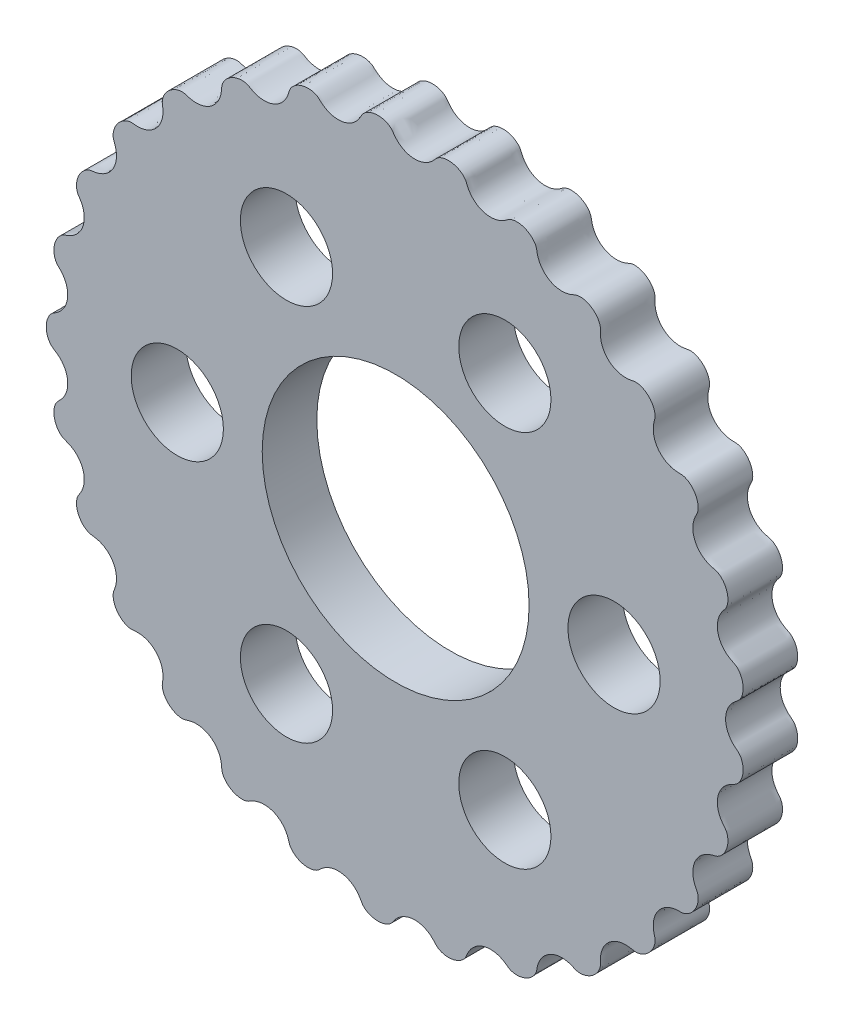
SolidWorks part; units mm, degrees
ref_plane "Front Plane" through (0, 0, 0) normal (0, 0, 1) x (1, 0, 0)
ref_plane "Top Plane" through (0, 0, 0) normal (0, 1, 0) x (1, 0, 0)
ref_plane "Right Plane" through (0, 0, 0) normal (1, 0, 0) x (0, 0, -1)
sketch "Sketch1" plane through (0, 0, 0) normal (0, 0, 1) x (1, 0, 0)
  line L0 (-108.3151, 0) -> (108.3151, 0) construction
  circle A8 centre (0, 0) radius 28.575 construction
  circle A9 centre (-28.575, 0) radius 6.0325
  circle A10 centre (-14.2875, 24.7467) radius 6.0325
  circle A11 centre (14.2875, 24.7467) radius 6.0325
  circle A12 centre (28.575, 0) radius 6.0325
  circle A13 centre (14.2875, -24.7467) radius 6.0325
  circle A14 centre (-14.2875, -24.7467) radius 6.0325
  circle A15 centre (0, 0) radius 17.4625
  spline S0 degree 4 number of poles 696 (10.649, 42.0128) -> (-34.5886, 28.7127) construction
  spline S1 degree 4 number of poles 415 (43.18, 0) -> (-45.72, 0) construction
  spline S2 degree 4 number of poles 414 (43.18, 0) -> (-45.72, 0) construction
  spline S3 degree 4 number of poles 846 (43.18, -0.0162) -> (43.18, -0.0162)
  point P4 (0, 0)
  point P23 (0, 0)
  point P25 (0, 0)
  dimension "D1" = 57.15
  dimension "D2" = 12.065
  dimension "D3" = 34.925
  dimension "D4" = 6
other "AlignGroup1"
extrude "Boss-Extrude1" add sketch "Sketch1" along normal blind 7.1437
